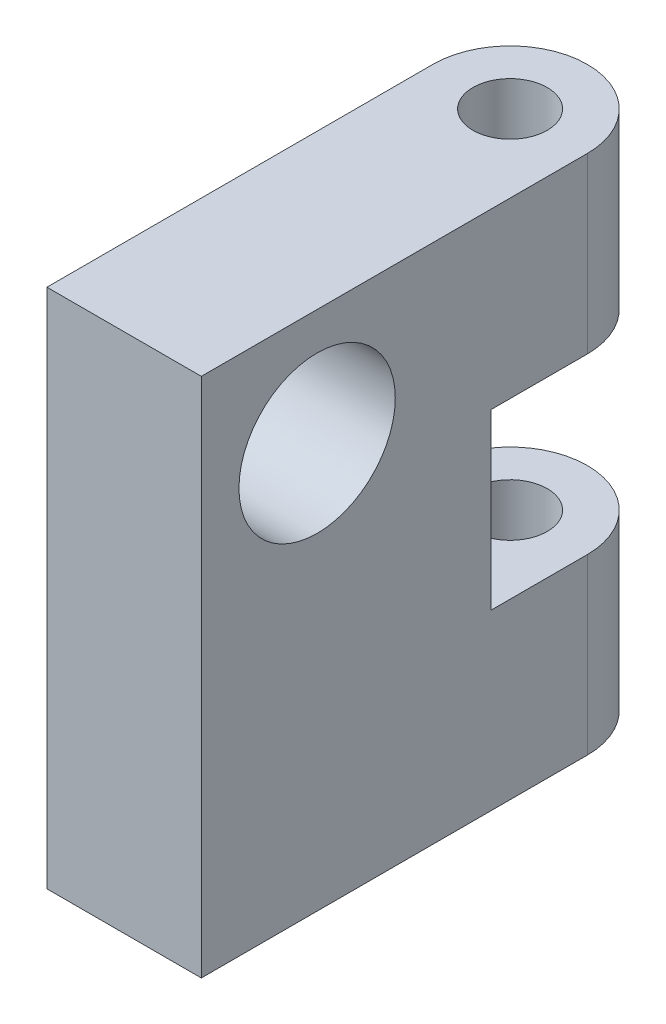
SolidWorks part; units mm, degrees
ref_plane "Front Plane" through (0, 0, 0) normal (0, 0, 1) x (1, 0, 0)
ref_plane "Top Plane" through (0, 0, 0) normal (0, 1, 0) x (1, 0, 0)
ref_plane "Right Plane" through (0, 0, 0) normal (1, 0, 0) x (0, 0, -1)
sketch "Sketch2" plane through (0, 0, 0) normal (0, 1, 0) x (1, 0, 0)
  line L0 (-4, 0) -> (-4, -20)
  line L1 (-4, -20) -> (4, -20)
  line L2 (4, 0) -> (4, -20)
  line L3 (4, -20) -> (3.9807, -20.0853)
  circle A0 centre (0, 0) radius 4
  circle A1 centre (0, 0) radius 1.925
  dimension "D1" = 8
  dimension "D2" = 3.85
  dimension "D3" = 20
extrude "Boss-Extrude1" add sketch "Sketch2" along normal blind 27 contours A0 A1 | A0 L0 L1 L2
sketch "Sketch3" plane through (4, 0, 0) normal (1, 0, 0) x (0, 0, -1)
  line L0 (0, 27) -> (-20, 27) construction
  line L1 (-20, 27) -> (-20, 0) construction
  circle A0 centre (-14, 21) radius 4.05
  dimension "D1" = 8.1
  dimension "D2" = 6
  dimension "D3" = 6
extrude "Cut-Extrude1" cut sketch "Sketch3" against normal blind 25
sketch "Sketch5" plane through (-4, 0, 0) normal (-1, 0, 0) x (0, 0, 1)
  line L0 (0, 0) -> (20, 0) construction
  line L1 (5, 18) -> (-4, 18)
  line L2 (5, 18) -> (5, 9)
  line L3 (5, 9) -> (-4, 9)
  line L4 (-4, 18) -> (-4, 9)
  line L5 (0, 27) -> (20, 27) construction
  line L6 (0, 27) -> (0, 0) construction
  dimension "D1" = 9
  dimension "D2" = 9
  dimension "D3" = 5
  dimension "D4" = 4
extrude "Cut-Extrude2" cut sketch "Sketch5" against normal blind 25
sketch "Sketch6" plane through (0, 0, 0) normal (0, -1, 0) x (-1, 0, 0)
  circle A0 centre (0, -15) radius 1.825
  circle A1 centre (0, 0) radius 1.925 construction
  dimension "D1" = 3.65
  dimension "D2" = 15
extrude "Cut-Extrude3" cut sketch "Sketch6" against normal blind 5
